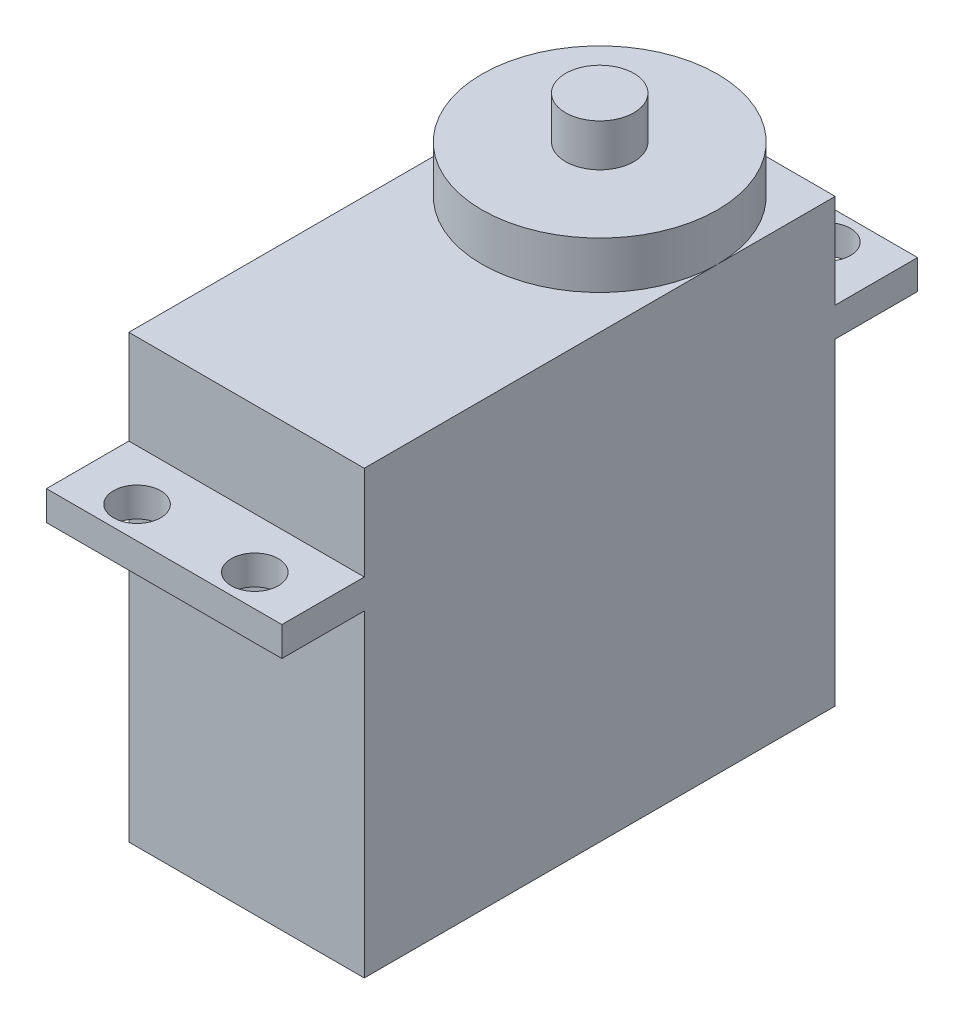
SolidWorks part; units mm, degrees
ref_plane "前视基准面" through (0, 0, 0) normal (0, 0, 1) x (1, 0, 0)
ref_plane "上视基准面" through (0, 0, 0) normal (0, 1, 0) x (1, 0, 0)
ref_plane "右视基准面" through (0, 0, 0) normal (1, 0, 0) x (0, 0, -1)
sketch "草图1" plane through (0, 0, 0) normal (0, 1, 0) x (1, 0, 0)
  line L1 (-10, 20) -> (10, 20)
  line L2 (-10, 20) -> (-10, -20)
  line L3 (-10, -20) -> (10, -20)
  line L4 (10, 20) -> (10, -20)
  line L5 (-10, 20) -> (10, -20) construction
  line L6 (-10, -20) -> (10, 20) construction
  point P0 (0, 0)
  dimension "D1" = 20
  dimension "D2" = 40
extrude "凸台-拉伸1" add sketch "草图1" along normal blind 27
sketch "草图2" plane through (0, 27, 0) normal (0, 1, 0) x (1, 0, 0)
  line L0 (-10, 20) -> (-10, -20) construction
  line L1 (-10, 27) -> (10, 27)
  line L2 (-10, 27) -> (-10, -27)
  line L3 (-10, -27) -> (10, -27)
  line L4 (10, 27) -> (10, -27)
  line L5 (-10, 27) -> (10, -27) construction
  line L6 (-10, -27) -> (10, 27) construction
  point P0 (0, 0)
  dimension "D1" = 54
extrude "凸台-拉伸2" add sketch "草图2" along normal blind 2.5
sketch "草图3" plane through (0, 29.5, 0) normal (0, 1, 0) x (1, 0, 0)
  line L0 (10, -27) -> (10, 27) construction
  line L1 (-10, 20) -> (10, 20)
  line L2 (-10, 20) -> (-10, -20)
  line L3 (-10, -20) -> (10, -20)
  line L4 (10, 20) -> (10, -20)
  line L5 (-10, 20) -> (10, -20) construction
  line L6 (-10, -20) -> (10, 20) construction
  line L7 (-10, -20) -> (10, -20) construction
  point P0 (0, 0)
extrude "凸台-拉伸3" add sketch "草图3" along normal offset from surface (8 mm away) 37.5 up to face at (0, 0, 0)
sketch "草图4" plane through (0, 29.5, 0) normal (0, 1, 0) x (1, 0, 0)
  line L0 (-5, 24.3) -> (-5, -24.3) construction
  line L1 (-5, -24.3) -> (5, -24.3) construction
  line L2 (5, -24.3) -> (5, 24.3) construction
  line L3 (5, 24.3) -> (-5, 24.3) construction
  line L4 (-10, 0) -> (10, 0) construction
  line L5 (-10, 20) -> (-10, -20) construction
  line L6 (10, -20) -> (10, 20) construction
  line L7 (0, 20) -> (0, -20) construction
  line L8 (10, 20) -> (-10, 20) construction
  line L9 (-10, -20) -> (10, -20) construction
  line L10 (10, 20) -> (-10, 20) construction
  circle A0 centre (-5, -24.3) radius 2
  circle A1 centre (5, -24.3) radius 2
  circle A2 centre (-5, 24.3) radius 2
  circle A3 centre (5, 24.3) radius 2
  point P14 (0, 0)
  dimension "D3" = 4
  dimension "D1" = 48.6
  dimension "D2" = 10
  dimension "D4" = 4.3
extrude "切除-拉伸1" cut sketch "草图4" against normal through all
sketch "草图5" plane through (0, 37.5, 0) normal (0, 1, 0) x (1, 0, 0)
  line L0 (-5, -24.3) -> (5, -24.3) construction
  line L1 (10, -20) -> (10, 20) construction
  line L2 (0, 10) -> (0, -24.3) construction
  circle A0 centre (0, 10) radius 10
  dimension "D1" = 34.3
extrude "凸台-拉伸4" add sketch "草图5" along normal blind 4
sketch "草图6" plane through (0, 41.5, 0) normal (0, 1, 0) x (1, 0, 0)
  circle A0 centre (0, 10) radius 2.9
  dimension "D1" = 5.8
extrude "凸台-拉伸5" add sketch "草图6" along normal blind 3.6
